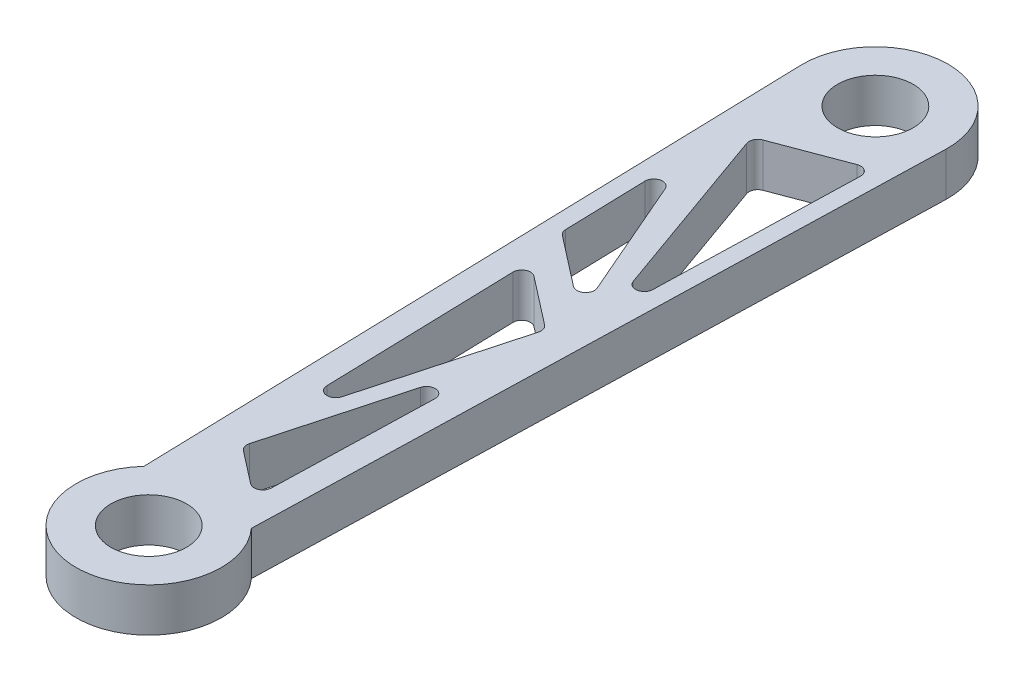
SolidWorks part; units mm, degrees
material "1060 合金"
ref_plane "前视基准面" through (0, 0, 0) normal (0, 0, 1) x (1, 0, 0)
ref_plane "上视基准面" through (0, 0, 0) normal (0, 1, 0) x (1, 0, 0)
ref_plane "右视基准面" through (0, 0, 0) normal (1, 0, 0) x (0, 0, -1)
sketch "草图1" plane through (0, 0, 0) normal (0, 1, 0) x (1, 0, 0)
  line L0 (0, 0) -> (0, 250) construction
  line L1 (-17.9929, -0.504) -> (-24.9902, 249.3)
  line L2 (17.9929, -0.504) -> (24.9902, 249.3)
  line L3 (-11.9953, -0.336) -> (-18.9926, 249.468) construction
  line L4 (11.9953, -0.336) -> (18.9926, 249.468) construction
  line L5 (-16.4444, 158.5) -> (15.7446, 133.5146) construction
  line L6 (15.7446, 133.5146) -> (18.4752, 231) construction
  line L7 (18.4752, 231) -> (-18.0888, 217.2024) construction
  line L8 (-18.0888, 217.2024) -> (-16.4444, 158.5) construction
  line L9 (15.7446, 133.5146) -> (-18.0888, 217.2024) construction
  line L10 (18.5259, 134.639) -> (-15.3075, 218.3268) construction
  line L11 (12.9633, 132.3901) -> (-20.8701, 216.0779) construction
  line L12 (-16.4444, 158.5) -> (-17.7049, 203.5)
  line L13 (-17.7049, 203.5) -> (11.0289, 137.1749)
  line L14 (11.0289, 137.1749) -> (-16.4444, 158.5)
  line L15 (15.9543, 141) -> (18.4752, 231)
  line L16 (-15.3075, 218.3268) -> (-13.7162, 214.3907) construction
  line L17 (18.4752, 231) -> (-12, 219.5)
  line L18 (-12, 219.5) -> (15.9543, 141)
  circle A0 centre (0, 250) radius 25 construction
  circle A1 centre (0, 0) radius 18 construction
  circle A2 centre (0, 0) radius 5.05
  circle A3 centre (0, 250) radius 13
  arc A4 (-17.9929, -0.504) -> (17.9929, -0.504) centre (0, 0) ccw
  arc A5 (-24.9902, 249.3) -> (24.9902, 249.3) centre (0, 250) cw
  arc A6 (-18.9926, 249.468) -> (18.9926, 249.468) centre (0, 250) cw construction
  arc A7 (-11.9953, -0.336) -> (11.9953, -0.336) centre (0, 0) ccw construction
  dimension "D2" = 50
  dimension "D3" = 36
  dimension "D4" = 10.1
  dimension "D5" = 26
  dimension "D1" = 250
  dimension "D9" = 19
  dimension "D10" = 30.5
  dimension "D11" = 16
  dimension "D12" = 45
  dimension "D13" = 90
  dimension "D14" = 12
  dimension "D6" = 6
  dimension "D7" = 3
  dimension "D8" = 3
extrude "凸台-拉伸1" add sketch "草图1" along normal blind 15
fillet "圆角1" radius 3 6 edges at (18.4752, 7.5, -231) (-12, 7.5, -219.5) (-17.7049, 7.5, -203.5) (-16.4444, 7.5, -158.5) (15.9543, 7.5, -141) (11.0289, 7.5, -137.1749)
sketch "草图2" plane through (0, 15, 0) normal (0, 1, 0) x (1, 0, 0)
  line L0 (0, 250) -> (-15, 250) construction
  circle A0 centre (-15, 250) radius 2
  dimension "D2" = 4
  dimension "D1" = 15
extrude "切除-拉伸1" [suppressed] cut sketch "草图2" against normal through all
pattern_circular "阵列(圆周)1" [suppressed] count 3 over 360
sketch "草图3" plane through (0, 15, 0) normal (0, 1, 0) x (1, 0, 0)
  line L0 (0, 250) -> (14.25, 250) construction
  circle A0 centre (14.25, 250) radius 2
  dimension "D2" = 4
  dimension "D1" = 14.25
extrude "切除-拉伸2" [suppressed] cut sketch "草图3" against normal through all
pattern_circular "阵列(圆周)2" [suppressed] count 3 over 360
sketch "草图4" plane through (0, 15, 0) normal (0, 1, 0) x (1, 0, 0)
  line L2 (8.9965, -0.252) -> (15.9937, 249.552)
  line L3 (8.9965, -0.252) -> (15.9937, 249.552) construction
  line L4 (-13.0503, 144.4724) -> (12.4949, 124.6439)
  line L5 (-15.9937, 249.552) -> (-8.9965, -0.252)
  line L6 (-15.9937, 249.552) -> (-8.9965, -0.252) construction
  line L7 (-15.3248, 157.6309) -> (1.7846, 144.3504) construction
  line L8 (12.4949, 124.6439) -> (9.7421, 26.3657)
  line L9 (9.7421, 26.3657) -> (-10.1751, 41.8256)
  line L10 (-10.1751, 41.8256) -> (-13.0503, 144.4724)
  dimension "D3" = 9
  dimension "D1" = 9
  dimension "D2" = 9
extrude "切除-拉伸3" cut sketch "草图4" against normal through all
fillet "圆角2" radius 3 3 edges at (9.7421, 7.5, -26.3657) (-10.1751, 7.5, -41.8256) (-13.0503, 7.5, -144.4724)
sketch "草图5" plane through (0, 15, 0) normal (0, 1, 0) x (1, 0, 0)
  circle A0 centre (0, 0) radius 27.5
  circle A1 centre (0, 0) radius 5.05
  dimension "D1" = 55
extrude "凸台-拉伸2" [suppressed] add sketch "草图5" against normal up to surface (10 mm away)
fillet "圆角3" [suppressed] radius 6
sketch "草图6" plane through (0, 15, 0) normal (0, 1, 0) x (1, 0, 0)
  line L0 (12.4949, 124.6439) -> (-10.1751, 41.8256) construction
  line L1 (-12.8725, 138.1249) -> (-10.2148, 43.2424) construction
  line L2 (9.6014, 125.4359) -> (-13.0687, 42.6176)
  line L3 (15.3885, 123.8518) -> (-7.2816, 41.0335)
  line L4 (-7.2816, 41.0335) -> (-7.6098, 39.8344)
  line L5 (-7.6098, 39.8344) -> (-13.0687, 42.6176)
  line L6 (9.6014, 125.4359) -> (9.9296, 126.6351)
  line L7 (9.9296, 126.6351) -> (15.3885, 123.8518)
  line L8 (-9.0555, 40.9565) -> (5.0694, 29.9927) construction
  line L9 (12.4949, 124.6439) -> (-8.0342, 140.5788) construction
  dimension "D1" = 3
  dimension "D2" = 3
extrude "凸台-拉伸3" add sketch "草图6" against normal up to surface (15 mm away) up to face at (-1.8624, 0, -78.5335)
fillet "圆角4" radius 3 4 edges at (12.1404, 7.5, -111.9858) (-10.4638, 7.5, -52.1336) (9.9296, 7.5, -126.6351) (-7.6098, 7.5, -39.8344)
sketch "草图7" plane through (0, 15, 0) normal (0, 1, 0) x (1, 0, 0)
  line L1 (15, 15) -> (-15, 15) construction
  line L2 (15, 15) -> (15, -15) construction
  line L3 (15, -15) -> (-15, -15) construction
  line L4 (-15, 15) -> (-15, -15) construction
  circle A0 centre (0, 0) radius 5.05 construction
  circle A1 centre (15, 15) radius 2.05
  circle A2 centre (-15, 15) radius 2.05
  circle A3 centre (-15, -15) radius 2.05
  circle A5 centre (15, -15) radius 2.05
  dimension "D2" = 15
  dimension "D4" = 4.1
  dimension "D1" = 30
  dimension "D3" = 15
extrude "切除-拉伸4" [suppressed] cut sketch "草图7" against normal through all
sketch "草图8" plane through (0, 15, 0) normal (0, 1, 0) x (1, 0, 0)
  circle A0 centre (0, 0) radius 13
  dimension "D1" = 26
extrude "切除-拉伸5" cut sketch "草图8" against normal through all
sketch "草图9" plane through (0, 15, 0) normal (0, 1, 0) x (1, 0, 0)
  circle A0 centre (0, 0) radius 25
  circle A1 centre (0, 0) radius 13
  circle A2 centre (0, 0) radius 13 construction
  dimension "D1" = 50
extrude "凸台-拉伸4" add sketch "草图9" against normal up to surface (15 mm away) up to face at (0, 0, 13)
